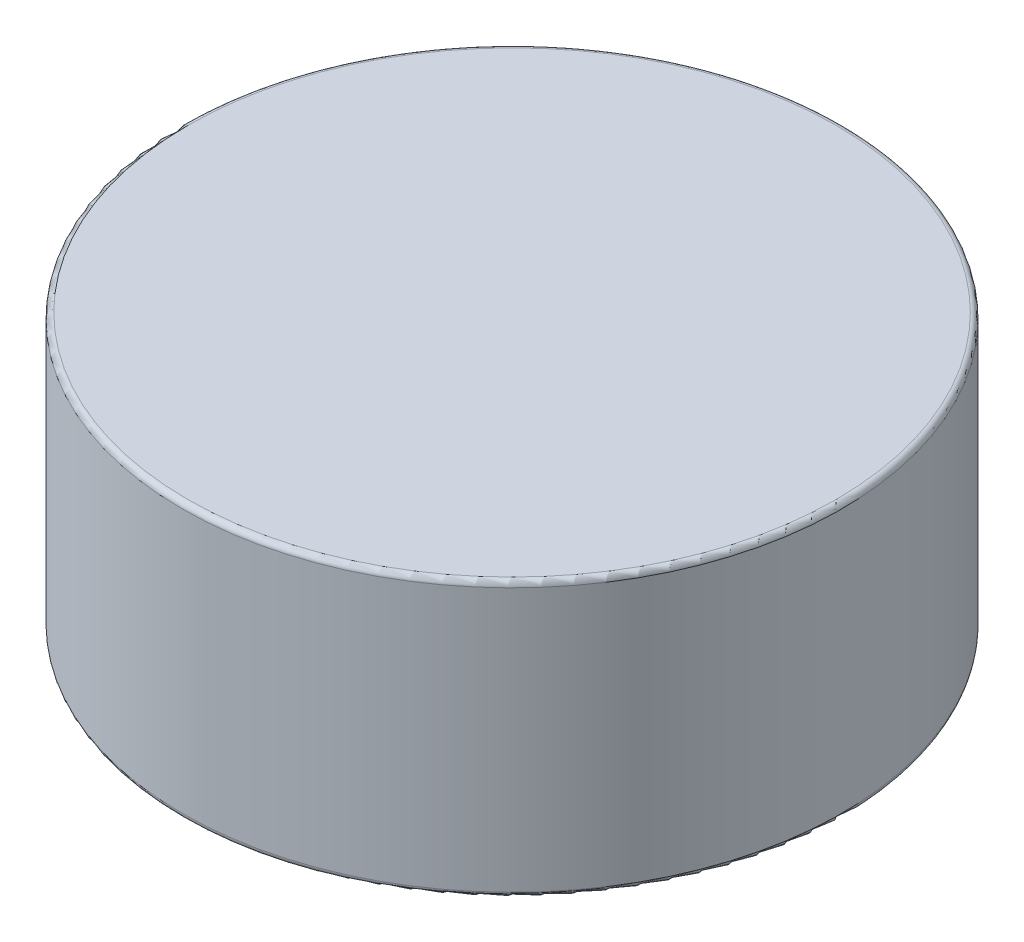
SolidWorks part; units mm, degrees
ref_plane "Спереди" through (0, 0, 0) normal (0, 0, 1) x (1, 0, 0)
ref_plane "Сверху" through (0, 0, 0) normal (0, 1, 0) x (1, 0, 0)
ref_plane "Справа" through (0, 0, 0) normal (1, 0, 0) x (0, 0, -1)
sketch "Эскиз1" plane through (0, 0, 0) normal (0, 1, 0) x (1, 0, 0)
  circle A0 centre (0, 0) radius 3
  dimension "D1" = 6
extrude "Бобышка-Вытянуть1" add sketch "Эскиз1" along normal blind 2.5
fillet "Скругление1" radius 0.05 1 edges at (0, 2.5, 3)
fillet "Скругление2" radius 0.05 1 edges at (0, 0, 3)
